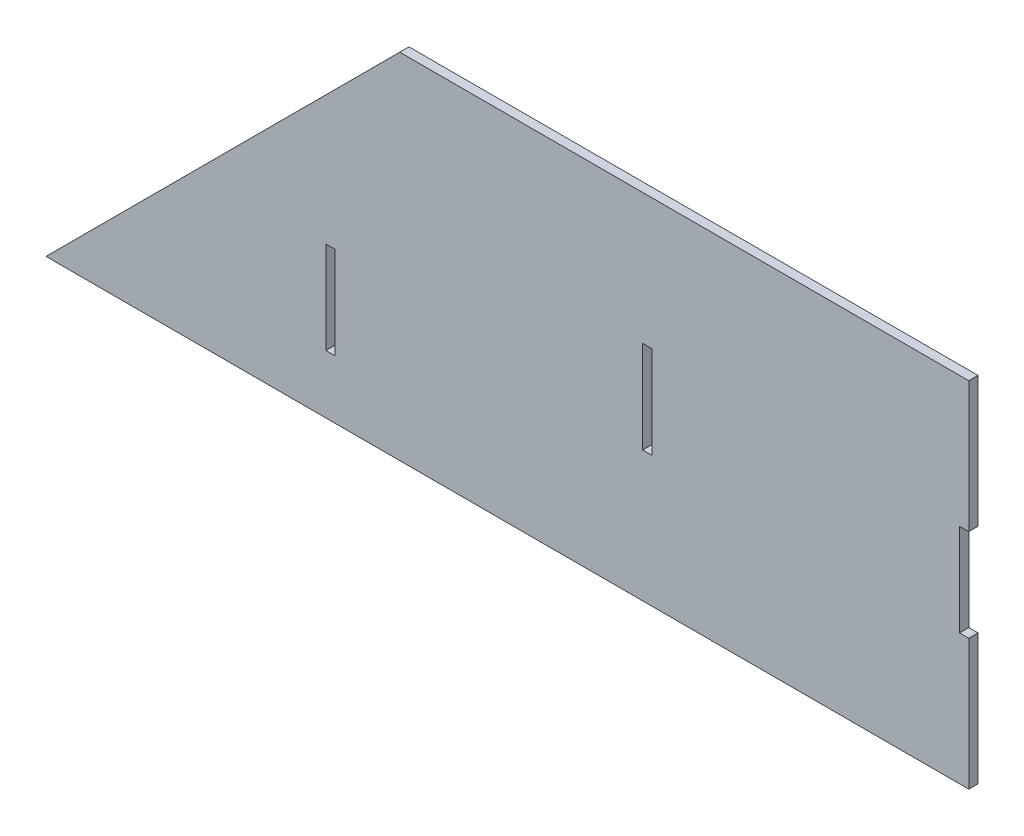
SolidWorks part; units mm, degrees
ref_plane "Front Plane" through (0, 0, 0) normal (0, 0, 1) x (1, 0, 0)
ref_plane "Top Plane" through (0, 0, 0) normal (0, 1, 0) x (1, 0, 0)
ref_plane "Right Plane" through (0, 0, 0) normal (1, 0, 0) x (0, 0, -1)
sketch "Sketch1" plane through (0, 0, 0) normal (0, 0, 1) x (1, 0, 0)
  line L21 (0, 0) -> (115, 115)
  line L22 (115, 115) -> (300, 115)
  line L24 (300, 0) -> (0, 0)
  line L25 (300, 115) -> (300, 72.5)
  line L26 (300, 72.5) -> (297, 72.5)
  line L27 (297, 72.5) -> (297, 42.5)
  line L28 (297, 42.5) -> (300, 42.5)
  line L29 (300, 42.5) -> (300, 0)
  line L30 (297, 57.5) -> (46.3855, 57.5) construction
  line L32 (197, 42.5) -> (194, 42.5)
  line L33 (197, 42.5) -> (197, 72.5)
  line L34 (197, 72.5) -> (194, 72.5)
  line L35 (194, 42.5) -> (194, 72.5)
  line L36 (197, 42.5) -> (194, 72.5) construction
  line L37 (197, 72.5) -> (194, 42.5) construction
  line L38 (94, 18.9921) -> (91, 18.9921)
  line L39 (94, 18.9921) -> (94, 48.9921)
  line L40 (94, 48.9921) -> (91, 48.9921)
  line L41 (91, 18.9921) -> (91, 48.9921)
  line L42 (94, 18.9921) -> (91, 48.9921) construction
  line L43 (94, 48.9921) -> (91, 18.9921) construction
  point P8 (195.5, 57.5)
  point P16 (291.0168, 42.5)
  point P17 (296.5828, 72.5)
  point P18 (92.5, 33.9921)
  point P23 (300.813, 72.5)
  dimension "D2" = 45
  dimension "D3" = 300
  dimension "D4" = 30
  dimension "D5" = 57.5
  dimension "D6" = 3
  dimension "D7" = 30
  dimension "D8" = 100
  dimension "D9" = 3
  dimension "D10" = 100
  dimension "D11" = 30
  dimension "D12" = 3
  dimension "D13" = 3
  dimension "D14" = 115
extrude "Boss-Extrude1" add sketch "Sketch1" along normal blind 3 contours L29 L28 L27 L26 L25 L22 L21 L24 L32 L35 L34 L33 L38 L41 L40 L39
